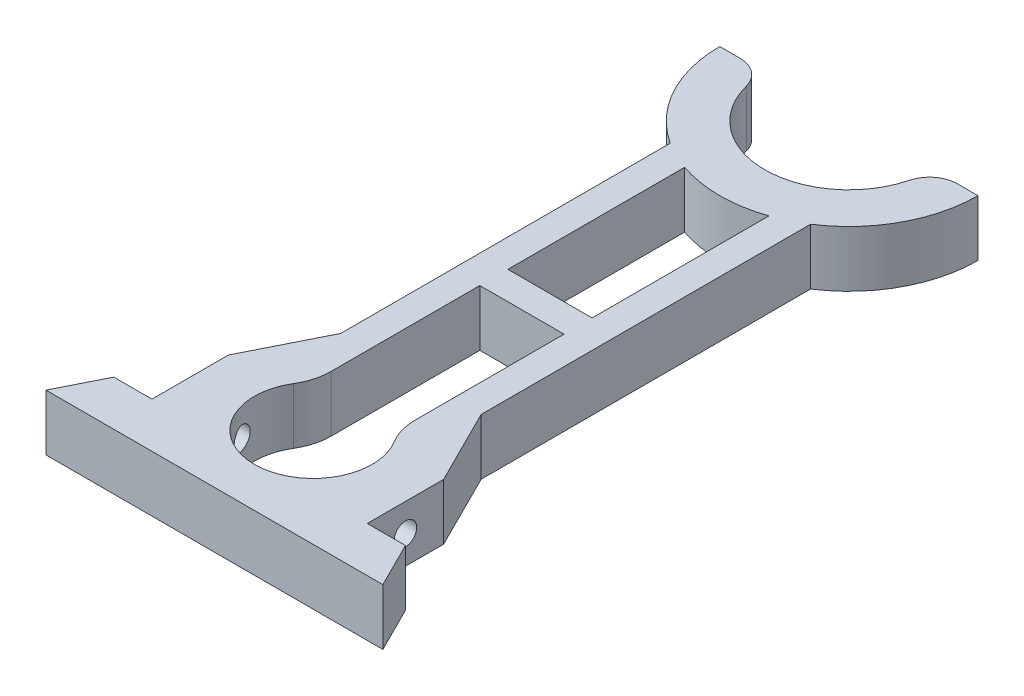
SolidWorks part; units mm, degrees
ref_plane "Front Plane" through (0, 0, 0) normal (0, 0, 1) x (1, 0, 0)
ref_plane "Top Plane" through (0, 0, 0) normal (0, 1, 0) x (1, 0, 0)
ref_plane "Right Plane" through (0, 0, 0) normal (1, 0, 0) x (0, 0, -1)
sketch "Sketch1" plane through (0, 0, 0) normal (0, 1, 0) x (1, 0, 0)
  line L0 (-15, 0) -> (-23, 0)
  line L5 (15, 0) -> (23, 0)
  line L6 (-12.5, -23) -> (-12.5, -19.3067)
  line L7 (12.5, -23) -> (12.5, -78)
  line L8 (12.5, -23) -> (12.5, -19.3067)
  line L9 (-12.5, -113) -> (12.5, -113)
  line L10 (-12.5, -23) -> (-12.5, -78)
  line L11 (12.5, -113) -> (30, -113)
  line L12 (-12.5, -113) -> (-30, -113)
  line L13 (0, -23) -> (0, -36.4836)
  line L14 (-7.5, -33.1809) -> (-7.5, -21.7428)
  line L15 (-7.5, -33.1809) -> (-7.5, -88.0491)
  line L16 (7.5, -33.1809) -> (7.5, -21.7428)
  line L17 (7.5, -33.1809) -> (7.5, -88.0491)
  line L18 (-12.5, -78) -> (-30, -113)
  line L19 (12.5, -78) -> (30, -113)
  line L20 (-30, -113) -> (-12.5, -113)
  line L21 (-30, -113) -> (-22.6502, -98.3003)
  arc A0 (-15, 0) -> (15, 0) centre (0, 0) ccw
  arc A1 (-23, 0) -> (-12.5, -19.3067) centre (0, 0) ccw
  arc A2 (-7.5, -21.7428) -> (7.5, -21.7428) centre (0, 0) ccw
  arc A3 (12.5, -19.3067) -> (23, 0) centre (0, 0) ccw
  arc A4 (-7.5, -88.0491) -> (7.5, -88.0491) centre (0, -95.3976) ccw
  point P5 (0, 0)
extrude "Boss-Extrude1" add sketch "Sketch1" along normal blind 10 contours L8 A3 L5 A0 L0 A1 L6 L10 L18 L12 L9 L11 L19 L7 A4 L15 L14 A2 L16 L17
fillet "Fillet1" radius 10 2 edges at (7.5, 5, 88.0491) (-7.5, 5, 88.0491)
fillet "Fillet2" radius 5 2 edges at (15, 5, 0) (-15, 5, 0)
sketch "Sketch6" plane through (0, 10, 0) normal (0, 1, 0) x (1, 0, 0)
  line L0 (19.1745, -91.349) -> (19.1745, -104.9541)
  line L1 (12.5, -78) -> (30, -113) construction
  line L2 (19.1745, -104.9541) -> (25.977, -104.9541)
  line L3 (0, -105.8976) -> (0, -94.1954)
  line L4 (19.1745, -91.349) -> (25.977, -104.9541)
  line L5 (-19.1745, -91.349) -> (-25.977, -104.9541)
  line L6 (-19.1745, -104.9541) -> (-25.977, -104.9541)
  line L7 (-19.1745, -91.349) -> (-19.1745, -104.9541)
  arc A0 (-8.9634, -89.9288) -> (8.9634, -89.9288) centre (0, -95.3976) ccw construction
  line M18 (-12.5, -78) -> (-30, -113)
  line M20 (30, -113) -> (12.5, -78)
extrude "Cut-Extrude1" cut sketch "Sketch6" against normal blind 10 contours L0 L2 M20 | L7 L6 M18
sketch "Sketch7" plane through (19.1745, 0, 0) normal (1, 0, 0) x (0, 0, -1)
  line L0 (-91.349, 10) -> (-91.349, 5)
  line L1 (-91.349, 0) -> (-91.349, 10) construction
  circle A0 centre (-98.1515, 5) radius 2
extrude "Cut-Extrude2" cut sketch "Sketch7" against normal blind 43 contours A0
sketch "Sketch8" plane through (0, 10, 0) normal (0, 1, 0) x (1, 0, 0)
  line L0 (-7.5, -53.2316) -> (7.5, -53.2316)
  line L1 (-7.5, -21.7428) -> (-7.5, -84.7205) construction
  line L2 (7.5, -84.7205) -> (7.5, -21.7428) construction
  line L3 (7.5, -53.2316) -> (7.5, -58.2316)
  line L4 (7.5, -58.2316) -> (-7.5, -58.2316)
  line L5 (-7.5, -58.2316) -> (-7.5, -53.2316)
extrude "Boss-Extrude3" add sketch "Sketch8" against normal blind 10
